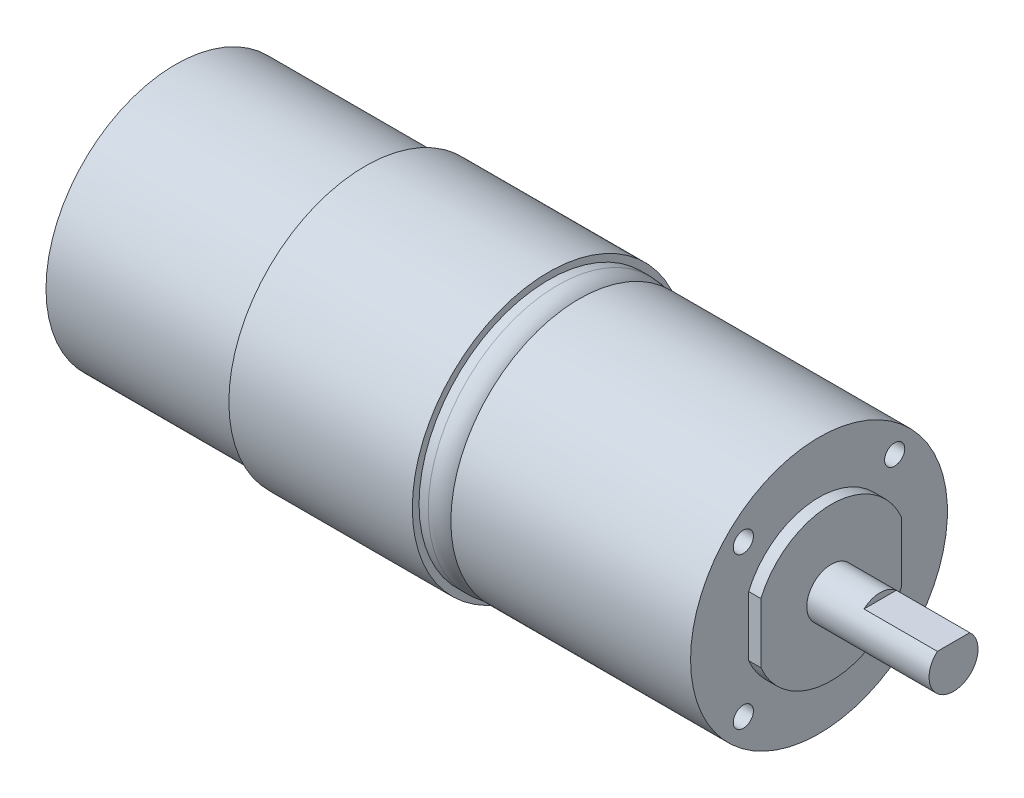
SolidWorks part; units mm, degrees
material "6061 Alloy"
ref_plane "Front Plane" through (0, 0, 0) normal (0, 0, 1) x (1, 0, 0)
ref_plane "Top Plane" through (0, 0, 0) normal (0, 1, 0) x (1, 0, 0)
ref_plane "Right Plane" through (0, 0, 0) normal (1, 0, 0) x (0, 0, -1)
sketch "Sketch1" plane through (0, 0, 0) normal (1, 0, 0) x (0, 0, -1)
  circle A0 centre (0, 0) radius 12.5
  dimension "D1" = 25
extrude "Boss-Extrude1" add sketch "Sketch1" against normal blind 2
sketch "Sketch3" plane through (-2, 0, 0) normal (-1, 0, 0) x (0, 0, 1)
  circle A0 centre (0, 0) radius 21
  dimension "D1" = 42
extrude "Boss-Extrude2" add sketch "Sketch3" along normal blind 39.2
sketch "Sketch4" plane through (-41.2, 0, 0) normal (-1, 0, 0) x (0, 0, 1)
  circle A0 centre (0, 0) radius 22.3
  dimension "D1" = 44.6
sketch "Sketch5" plane through (-41.2, 0, 0) normal (-1, 0, 0) x (0, 0, 1)
  circle A0 centre (0, 0) radius 21.2
  dimension "D1" = 42.4
extrude "Boss-Extrude3" add sketch "Sketch5" along normal blind 66 separate body
fillet "Fillet1" radius 3.5 1 edges at (-41.2, 0, 21.2)
extrude "Boss-Extrude4" add sketch "Sketch4" along normal blind 30 from offset 5
sketch "Sketch6" plane through (0, 0, 0) normal (1, 0, 0) x (0, 0, -1)
  circle A0 centre (0, 0) radius 4
  dimension "D1" = 8
extrude "Boss-Extrude5" add sketch "Sketch6" along normal blind 20
sketch "Sketch7" plane through (20, 0, 0) normal (1, 0, 0) x (0, 0, -1)
  line L1 (-2.6458, 5) -> (2.6458, 5)
  line L2 (-2.6458, 5) -> (-2.6458, 3)
  line L3 (-2.6458, 3) -> (2.6458, 3)
  line L4 (2.6458, 5) -> (2.6458, 3)
  line L5 (-2.6458, 5) -> (2.6458, 3) construction
  line L6 (-2.6458, 3) -> (2.6458, 5) construction
  circle A0 centre (0, 0) radius 4 construction
  point P0 (0, 4)
  dimension "D1" = 7
extrude "Cut-Extrude1" cut sketch "Sketch7" against normal blind 12
hole_wizard "M4x0.7 \"M4x6DP\"" positions "Sketch9" profile "Sketch10" tap size "M4x0.7" standard "ANSI Metric"
sketch "Sketch9" plane through (-2, 0, 0) normal (1, 0, 0) x (0, 0, -1)
  line L1 (-12.3744, -12.3744) -> (12.3744, -12.3744)
  line L2 (-12.3744, -12.3744) -> (-12.3744, 12.3744)
  line L3 (-12.3744, 12.3744) -> (12.3744, 12.3744)
  line L4 (12.3744, -12.3744) -> (12.3744, 12.3744)
  line L5 (-12.3744, -12.3744) -> (12.3744, 12.3744) construction
  line L6 (-12.3744, 12.3744) -> (12.3744, -12.3744) construction
  circle A0 centre (0, 0) radius 17.5
  point P57 (-12.3744, 12.3744)
  point P59 (12.3744, 12.3744)
  point P61 (12.3744, -12.3744)
  point P63 (-12.3744, -12.3744)
  dimension "D1" = 35
sketch "Sketch10" plane through (-2, 12.3744, 12.3744) normal (0, 1, 0) x (0, 0, -1)
  line L0 (0, 0) -> (0, 11.0914)
  line L1 (0, 11.0914) -> (1.65, 10.1)
  line L2 (1.65, 10.1) -> (1.65, 0)
  line L5 (1.65, 0) -> (0, 0)
  line L10 (0, 11.0914) -> (-1.65, 10.1) construction
  line L11 (0, -6.35) -> (0, 107.95) construction
  dimension "Tap Drill Dia." = 3.3
  dimension "Tap Drill Depth" = 10.1
  dimension "Drill Angle" = 118
cosmetic thread "Hole Thread1" parameters "D1"=8, "D2"=4
cosmetic thread "Hole Thread2" parameters "D1"=8, "D2"=4
cosmetic thread "Hole Thread3" parameters "D1"=8, "D2"=4
cosmetic thread "Hole Thread4" parameters "D1"=8, "D2"=4
sketch "Sketch11" plane through (0, 0, 0) normal (1, 0, 0) x (0, 0, -1)
  line L1 (11.5, -12.5) -> (-11.5, -12.5)
  line L2 (11.5, -12.5) -> (11.5, 12.5)
  line L3 (11.5, 12.5) -> (-11.5, 12.5)
  line L4 (-11.5, -12.5) -> (-11.5, 12.5)
  line L5 (11.5, -12.5) -> (-11.5, 12.5) construction
  line L6 (11.5, 12.5) -> (-11.5, -12.5) construction
  circle A0 centre (0, 0) radius 12.5 construction
  point P0 (0, 0)
  dimension "D1" = 23
extrude "Cut-Extrude2" cut sketch "Sketch11" against normal up to surface (2 mm away) flip side to cut up to face at (-2, 12.3744, 10.7244)
